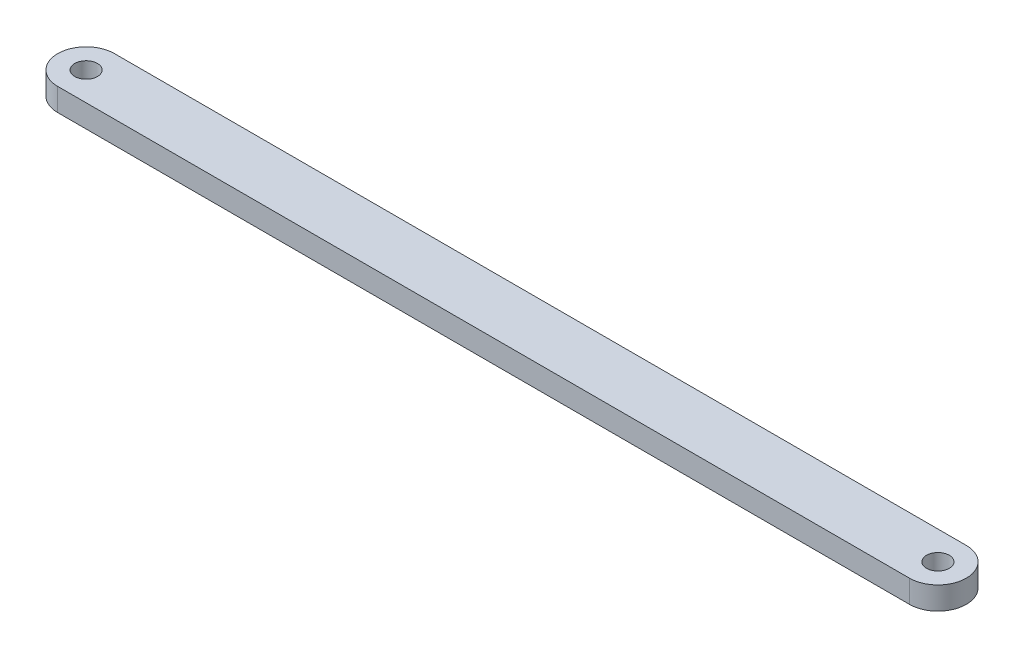
SolidWorks part; units mm, degrees
ref_plane "Front Plane" through (0, 0, 0) normal (0, 0, 1) x (1, 0, 0)
ref_plane "Top Plane" through (0, 0, 0) normal (0, 1, 0) x (1, 0, 0)
ref_plane "Right Plane" through (0, 0, 0) normal (1, 0, 0) x (0, 0, -1)
sketch "Sketch1" plane through (0, 0, 0) normal (0, 1, 0) x (1, 0, 0)
  line L0 (-10, 0) -> (65, 0) construction
  line L1 (-10, 2.5) -> (65, 2.5)
  line L2 (-10, -2.5) -> (65, -2.5)
  arc A0 (-10, 2.5) -> (-10, -2.5) centre (-10, 0) ccw
  arc A1 (65, -2.5) -> (65, 2.5) centre (65, 0) ccw
  circle A2 centre (65, 0) radius 1
  circle A3 centre (-10, 0) radius 1
  point P3 (27.5, 0)
  dimension "D3" = 2
  dimension "D4" = 2.5
  dimension "D5" = 2
  dimension "D1" = 75
  dimension "D12" = 10
extrude "Boss-Extrude1" add sketch "Sketch1" along normal blind 2
